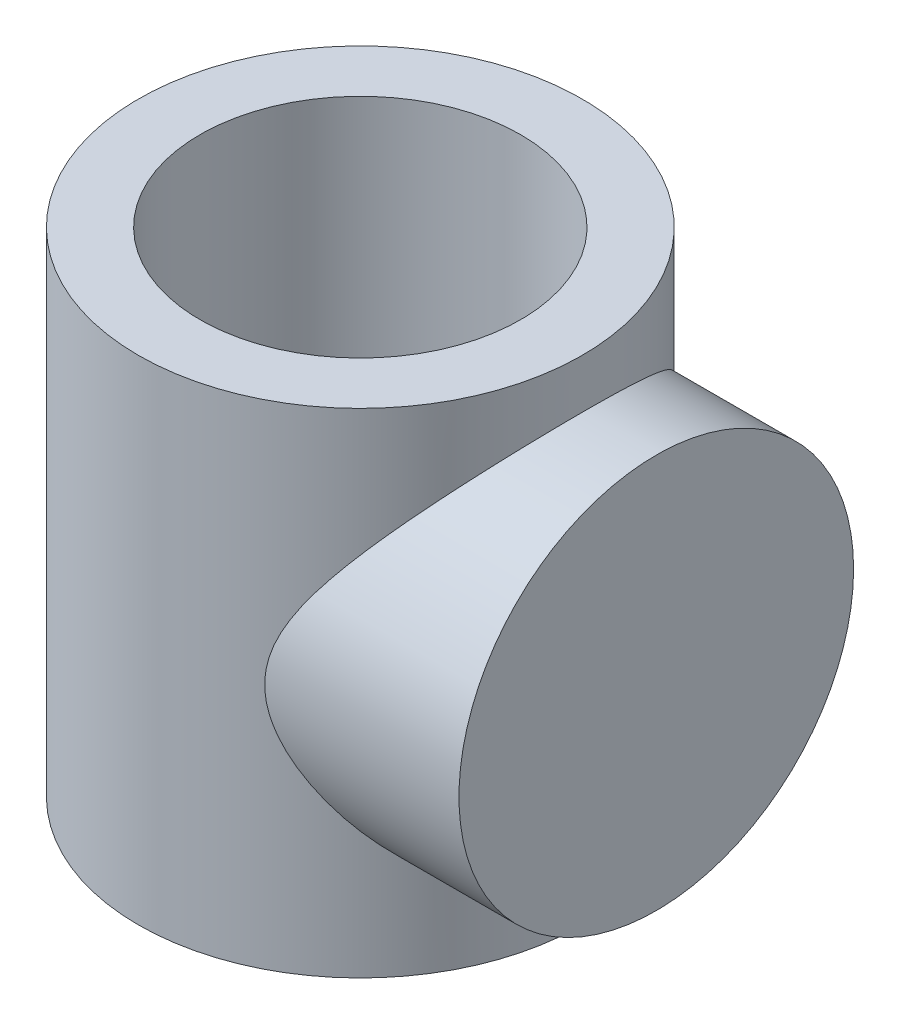
SolidWorks part; units mm, degrees
ref_plane "Front Plane" through (0, 0, 0) normal (0, 0, 1) x (1, 0, 0)
ref_plane "Top Plane" through (0, 0, 0) normal (0, 1, 0) x (1, 0, 0)
ref_plane "Right Plane" through (0, 0, 0) normal (1, 0, 0) x (0, 0, -1)
sketch "Sketch1" plane through (0, 0, 0) normal (0, 1, 0) x (1, 0, 0)
  circle A0 centre (0, 0) radius 45
  circle A1 centre (0, 0) radius 32.5
  dimension "D1" = 90
  dimension "D2" = 65
extrude "Boss-Extrude1" add sketch "Sketch1" along normal blind 100
ref_plane "Plane1" through (60, 0, 0) normal (1, 0, 0) x (0, 0, -1)
sketch "Sketch2" plane through (60, 0, 0) normal (1, 0, 0) x (0, 0, -1)
  circle A0 centre (0, 50) radius 40
  dimension "D1" = 80
  dimension "D2" = 50
extrude "Boss-Extrude2" add sketch "Sketch2" against normal up to surface (39.3845 mm away)
